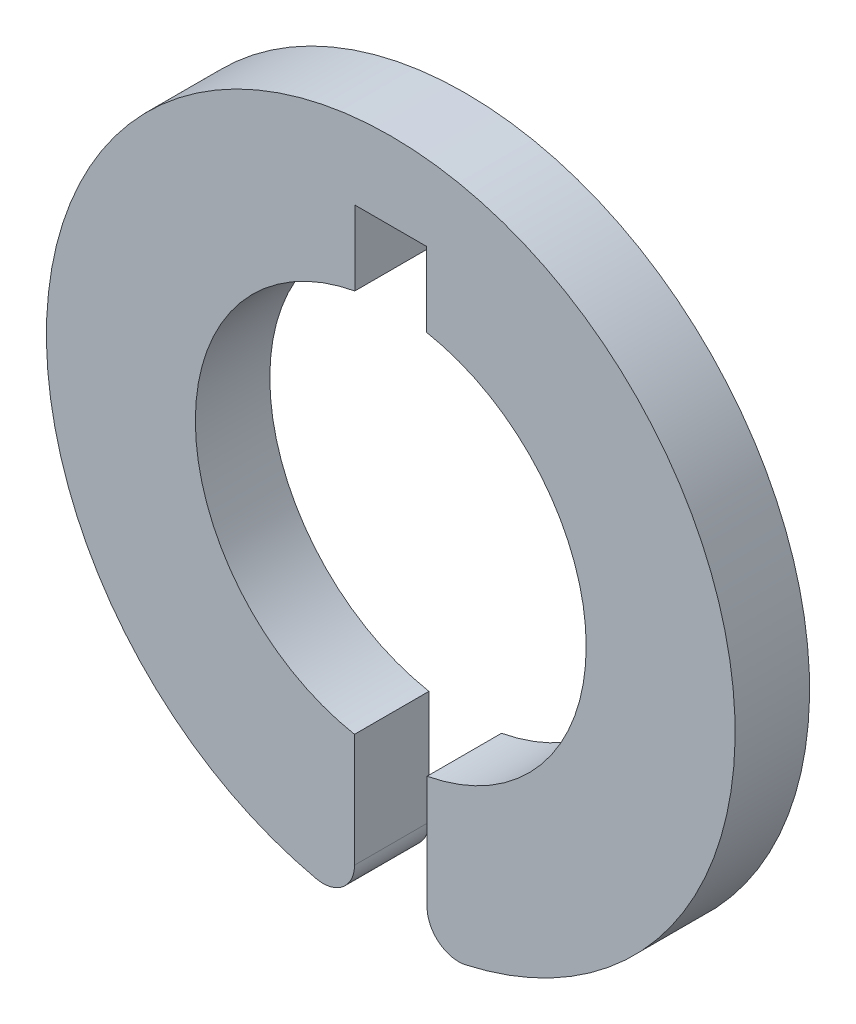
SolidWorks part; units mm, degrees
material "Acrylic (Medium-high impact)"
ref_plane "Front Plane" through (0, 0, 0) normal (0, 0, 1) x (1, 0, 0)
ref_plane "Top Plane" through (0, 0, 0) normal (0, 1, 0) x (1, 0, 0)
ref_plane "Right Plane" through (0, 0, 0) normal (1, 0, 0) x (0, 0, -1)
sketch "스케치1" plane through (0, 0, 0) normal (0, 0, 1) x (1, 0, 0)
  line L0 (0, 10.85) -> (0, 0) construction
  line L6 (-1.4475, 10.7398) -> (1.4475, 10.7398)
  line L7 (0, 0) -> (0, -10.7668) construction
  line L8 (-1.4625, -13.7967) -> (1.4625, -13.7967) construction
  line L9 (-1.4625, -13.7967) -> (-1.4625, -7.737)
  line L10 (-1.4625, -7.737) -> (1.4625, -7.737) construction
  line L11 (1.4625, -13.7967) -> (1.4625, -7.737)
  line L12 (-1.4625, -13.7967) -> (1.4625, -7.737) construction
  line L13 (-1.4625, -7.737) -> (1.4625, -13.7967) construction
  line L14 (-1.4475, 10.7398) -> (-1.4475, 7.7398)
  line L15 (-1.4475, 7.7398) -> (1.4475, 7.7398) construction
  line L16 (1.4475, 10.7398) -> (1.4475, 7.7398)
  line L17 (-1.4475, 10.7398) -> (1.4475, 7.7398) construction
  line L18 (-1.4475, 7.7398) -> (1.4475, 10.7398) construction
  circle A0 centre (0, 0) radius 13.874 construction
  circle A1 centre (0, 0) radius 7.874 construction
  arc A2 (-1.4625, -13.7967) -> (1.4625, -13.7967) centre (0, 0) cw
  arc A3 (1.4625, -7.737) -> (1.4475, 7.7398) centre (0, 0) ccw
  arc A4 (-1.4475, 7.7398) -> (-1.4625, -7.737) centre (0, 0) ccw
  point P2 (0, 10.85)
  point P5 (0, 9.2398)
  point P10 (0, -10.7668)
  dimension "D1" = 6
  dimension "D2" = 15.748
  dimension "D3" = 2.895
  dimension "D4" = 3
  dimension "D5" = 2.925
extrude "보스-돌출1" add sketch "스케치1" along normal blind 3
fillet "필렛1" radius 1.27 2 edges at (1.4625, -13.7967, 1.5) (-1.4625, -13.7967, 1.5)
